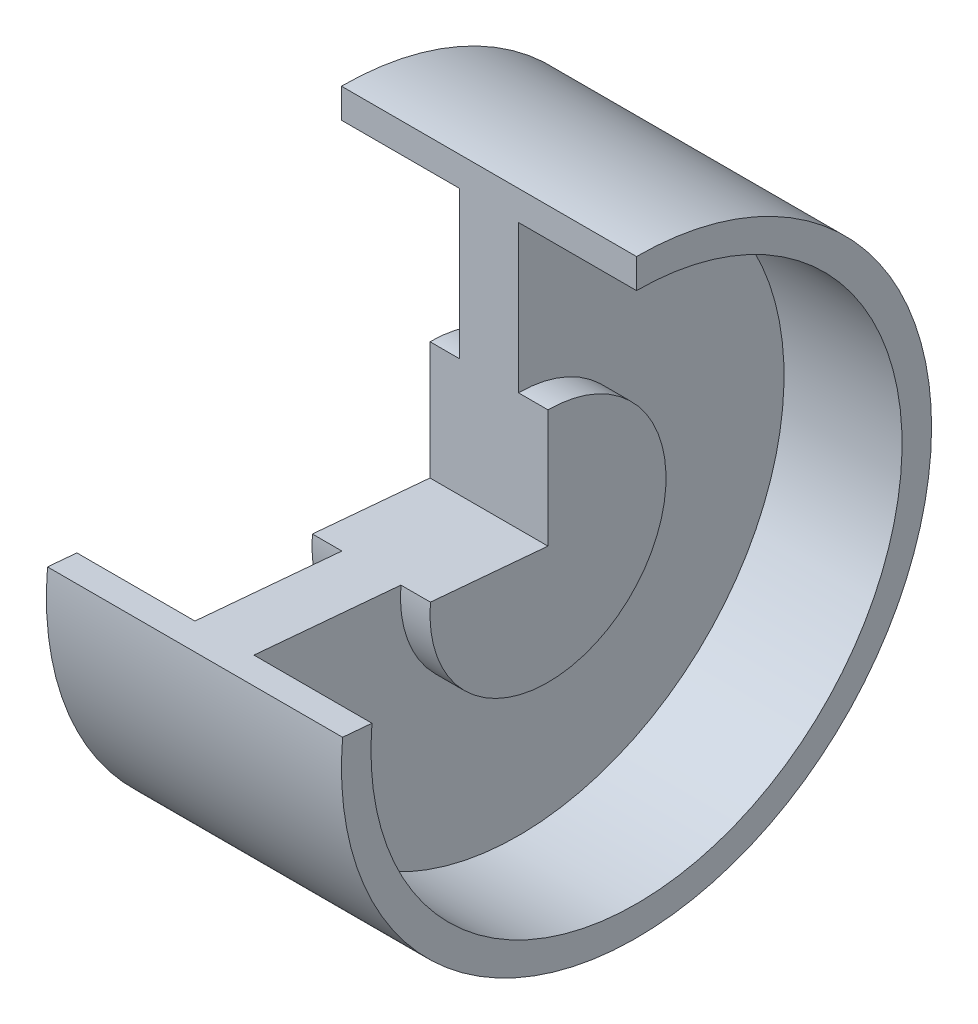
SolidWorks part; units mm, degrees
ref_plane "Front Plane" through (0, 0, 0) normal (0, 0, 1) x (1, 0, 0)
ref_plane "Top Plane" through (0, 0, 0) normal (0, 1, 0) x (1, 0, 0)
ref_plane "Right Plane" through (0, 0, 0) normal (1, 0, 0) x (0, 0, -1)
sketch "Sketch1" plane through (0, 0, 0) normal (0, 0, 1) x (1, 0, 0)
  line L0 (0, 0) -> (18884.9812, 0) construction
  line L1 (0, 0) -> (0, 18884.9812) construction
  line L2 (-10, 0) -> (10, 0)
  line L3 (10, 0) -> (10, 20)
  line L4 (10, 20) -> (5, 20)
  line L5 (5, 20) -> (5, 45)
  line L6 (5, 45) -> (25, 45)
  line L7 (25, 45) -> (25, 50)
  line L8 (25, 50) -> (-25, 50)
  line L9 (0, 0) -> (-18884.9812, 0) construction
  line L10 (-25, 45) -> (-25, 50)
  line L11 (-5, 45) -> (-25, 45)
  line L12 (-5, 20) -> (-5, 45)
  line L13 (-10, 20) -> (-5, 20)
  line L14 (-10, 0) -> (-10, 20)
  point P5 (10, 9.0875)
  point P16 (0, 50)
  point P21 (0, 0)
  dimension "D1" = 20
  dimension "D2" = 10
  dimension "D3" = 50
  dimension "D4" = 5
  dimension "D5" = 25
revolve "Revolve1" add sketch "Sketch1" angle 275 about L0
